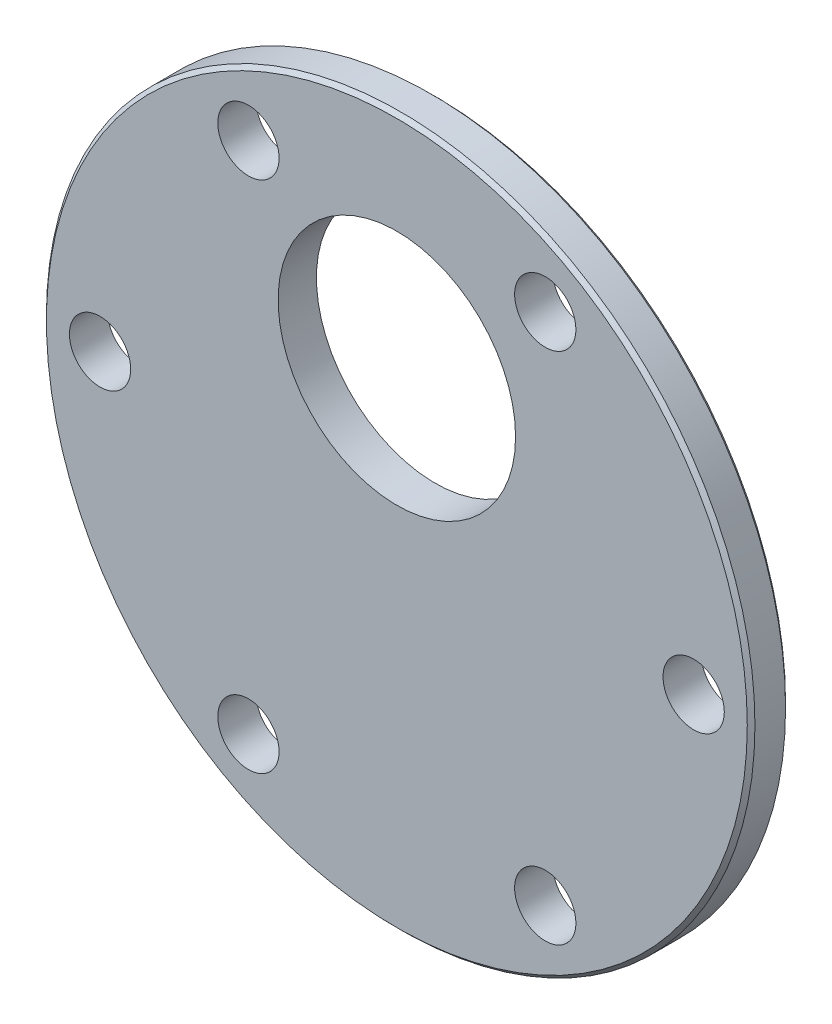
SolidWorks part; units mm, degrees
ref_plane "前视基准面" through (0, 0, 0) normal (0, 0, 1) x (1, 0, 0)
ref_plane "上视基准面" through (0, 0, 0) normal (0, 1, 0) x (1, 0, 0)
ref_plane "右视基准面" through (0, 0, 0) normal (1, 0, 0) x (0, 0, -1)
sketch "草图1" plane through (0, 0, 0) normal (0, 0, 1) x (1, 0, 0)
  line L0 (0, 0) -> (0, -7) construction
  line L1 (0, -7) -> (15.5, -7) construction
  line L2 (0, -7) -> (7.75, -20.4234) construction
  line L3 (0, -7) -> (-7.75, -20.4234) construction
  line L4 (0, -7) -> (-15.5, -7) construction
  line L5 (0, -7) -> (-7.75, 6.4234) construction
  line L6 (0, -7) -> (7.75, 6.4234) construction
  circle A0 centre (0, 0) radius 6.2
  circle A1 centre (15.5, -7) radius 1.6
  circle A2 centre (7.75, -20.4234) radius 1.6
  circle A3 centre (-7.75, -20.4234) radius 1.6
  circle A4 centre (-15.5, -7) radius 1.6
  circle A5 centre (-7.75, 6.4234) radius 1.6
  circle A6 centre (7.75, 6.4234) radius 1.6
  circle A7 centre (0, -7) radius 18.5
  point P18 (0, -7)
  dimension "D1" = 12.4
  dimension "D4" = 3.2
  dimension "D6" = 37
  dimension "D2" = 7
  dimension "D3" = 15.5
  dimension "D5" = 6
extrude "凸台-拉伸1" add sketch "草图1" along normal blind 2
chamfer "倒角1" distance 0.2 angle 45 2 edges at (18.5, -7, 0) (18.5, -7, 2)
